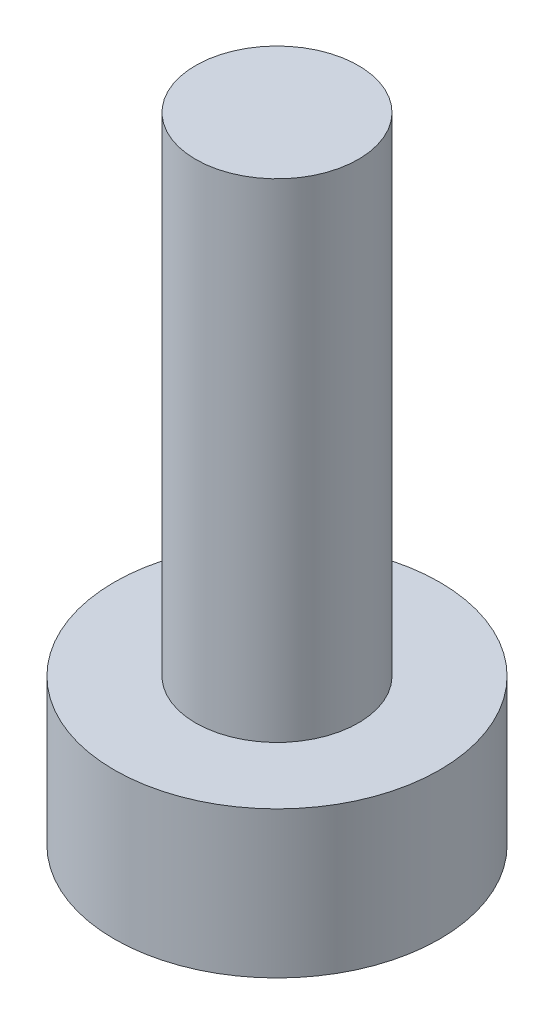
SolidWorks part; units mm, degrees
ref_plane "Front Plane" through (0, 0, 0) normal (0, 0, 1) x (1, 0, 0)
ref_plane "Top Plane" through (0, 0, 0) normal (0, 1, 0) x (1, 0, 0)
ref_plane "Right Plane" through (0, 0, 0) normal (1, 0, 0) x (0, 0, -1)
sketch "Sketch1" plane through (0, 0, 0) normal (0, 1, 0) x (1, 0, 0)
  circle A0 centre (0, 0) radius 3
  dimension "D1" = 6
extrude "Boss-Extrude1" add sketch "Sketch1" along normal blind 2.7
sketch "Sketch2" plane through (0, 2.7, 0) normal (0, 1, 0) x (1, 0, 0)
  circle A0 centre (0, 0) radius 1.5
  dimension "D1" = 3
extrude "Boss-Extrude2" add sketch "Sketch2" along normal blind 9
